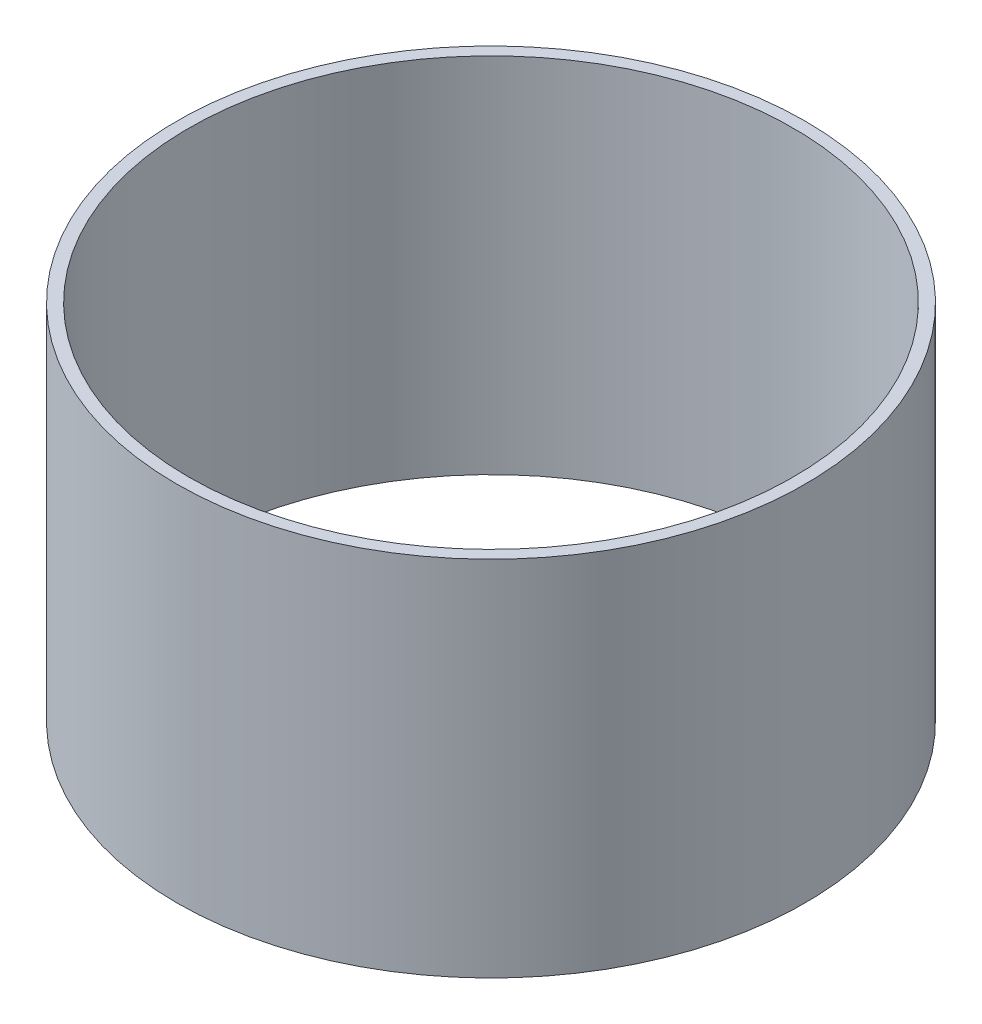
SolidWorks part; units mm, degrees
ref_plane "Front Plane" through (0, 0, 0) normal (0, 0, 1) x (1, 0, 0)
ref_plane "Top Plane" through (0, 0, 0) normal (0, 1, 0) x (1, 0, 0)
ref_plane "Right Plane" through (0, 0, 0) normal (1, 0, 0) x (0, 0, -1)
sketch "Sketch1" plane through (0, 0, 0) normal (0, 1, 0) x (1, 0, 0)
  circle A0 centre (0, 0) radius 26
  circle A1 centre (0, 0) radius 25
  dimension "D1" = 52
  dimension "D2" = 50
extrude "Boss-Extrude1" add sketch "Sketch1" along normal blind 30
